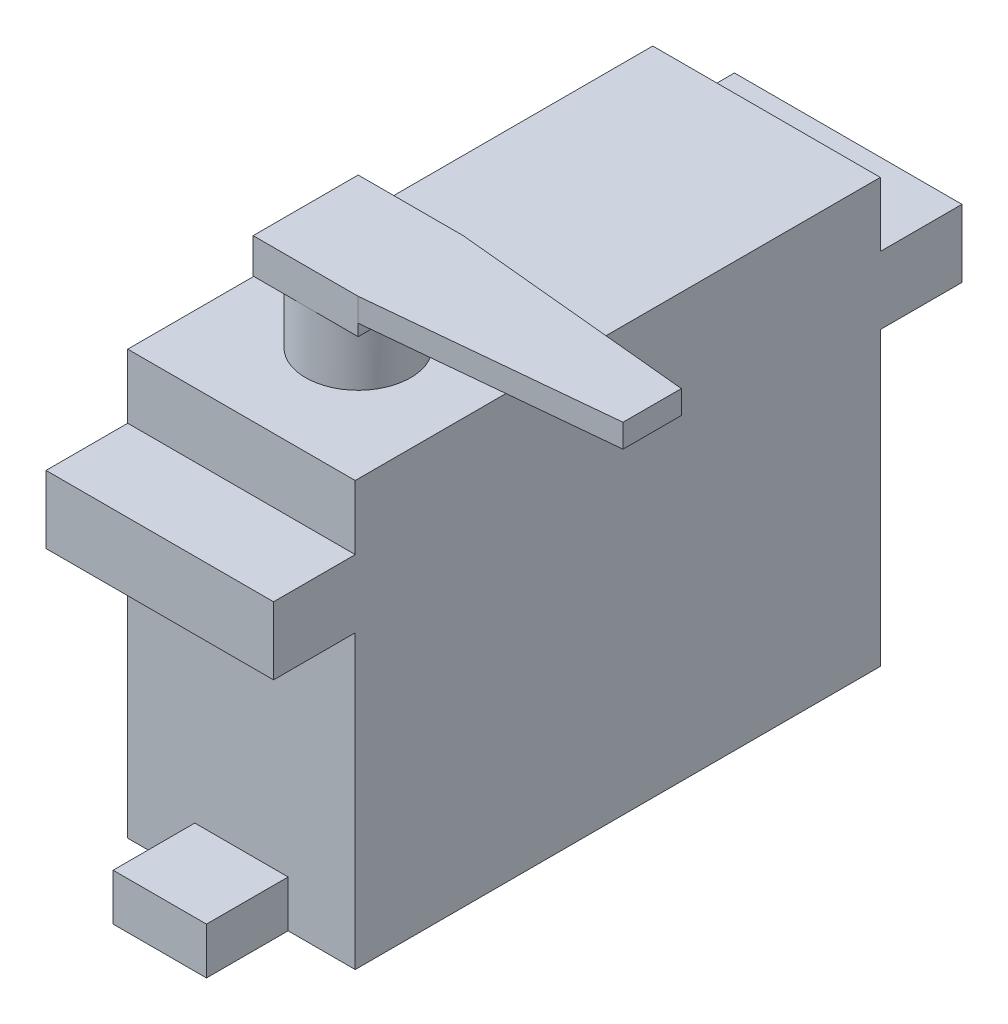
SolidWorks part; units mm, degrees
ref_plane "Front Plane" through (0, 0, 0) normal (0, 0, 1) x (1, 0, 0)
ref_plane "Top Plane" through (0, 0, 0) normal (0, 1, 0) x (1, 0, 0)
ref_plane "Right Plane" through (0, 0, 0) normal (1, 0, 0) x (0, 0, -1)
sketch "Sketch1" plane through (0, 0, 0) normal (1, 0, 0) x (0, 0, -1)
  line L0 (0, 0) -> (45, 0)
  line L1 (45, 0) -> (45, 25)
  line L2 (45, 25) -> (52, 25)
  line L3 (52, 25) -> (52, 30.8)
  line L4 (52, 30.8) -> (45, 30.8)
  line L5 (45, 30.8) -> (45, 36.3)
  line L6 (45, 36.3) -> (0, 36.3)
  line L7 (0, 36.3) -> (0, 30.8)
  line L8 (0, 30.8) -> (-7, 30.8)
  line L9 (-7, 30.8) -> (-7, 25)
  line L10 (-7, 25) -> (0, 25)
  line L11 (0, 25) -> (0, 0)
  dimension "D1" = 45
  dimension "D2" = 25
  dimension "D3" = 7
  dimension "D4" = 5.8
  dimension "D5" = 5.5
  dimension "D6" = 7
  dimension "D7" = 5.8
  dimension "D8" = 45
  dimension "D9" = 25
extrude "Boss-Extrude1" add sketch "Sketch1" along normal blind 19.5
sketch "Sketch2" plane through (0, 0, 0) normal (0, 0, 1) x (1, 0, 0)
  line L0 (0, 0) -> (9.75, 0) construction
  line L1 (19.5, 0) -> (0, 0) construction
  line L2 (9.75, 0) -> (9.75, 4) construction
  line L3 (9.75, 4) -> (5.75, 4) construction
  line L5 (5.75, 4) -> (13.75, 4)
  line L6 (5.75, 4) -> (5.75, 0)
  line L7 (5.75, 0) -> (13.75, 0)
  line L8 (13.75, 4) -> (13.75, 0)
  dimension "D1" = 4
  dimension "D2" = 4
  dimension "D3" = 8
extrude "Boss-Extrude2" add sketch "Sketch2" along normal blind 7
sketch "Sketch3" plane through (0, 36.3, 0) normal (0, 1, 0) x (1, 0, 0)
  line L0 (0, 45) -> (0, 0) construction
  line L1 (19.5, 0) -> (0, 0) construction
  circle A0 centre (9.75, 10) radius 4.5
  dimension "D3" = 9
  dimension "D1" = 9.75
  dimension "D2" = 10
extrude "Boss-Extrude3" add sketch "Sketch3" along normal blind 5.3 contours A0
sketch "Sketch4" plane through (0, 41.6, 0) normal (0, 1, 0) x (1, 0, 0)
  line L1 (14.25, 5.5) -> (5.25, 5.5)
  line L2 (14.25, 5.5) -> (14.25, 14.5)
  line L3 (14.25, 14.5) -> (5.25, 14.5)
  line L4 (5.25, 5.5) -> (5.25, 14.5)
  line L5 (14.25, 5.5) -> (5.25, 14.5) construction
  line L6 (14.25, 14.5) -> (5.25, 5.5) construction
  point P0 (9.75, 10)
  dimension "D1" = 9
extrude "Boss-Extrude4" add sketch "Sketch4" along normal blind 1
sketch "Sketch5" plane through (0, 42.6, 0) normal (0, 1, 0) x (1, 0, 0)
  line L0 (14.25, 5.5) -> (14.25, 14.5) construction
  line L1 (5.25, 14.5) -> (14.25, 14.5)
  line L2 (5.25, 14.5) -> (5.25, 5.5)
  line L3 (5.25, 5.5) -> (14.25, 5.5)
  line L5 (5.25, 10) -> (34.95, 10) construction
  line L6 (34.95, 10) -> (34.95, 12.5)
  line L7 (34.95, 12.5) -> (14.25, 14.5)
  line L8 (34.95, 10) -> (34.95, 7.5)
  line L9 (14.25, 5.5) -> (34.95, 7.5)
  dimension "D1" = 29.7
  dimension "D2" = 2.5
  dimension "D3" = 2.5
  dimension "D4" = 2
extrude "Boss-Extrude5" add sketch "Sketch5" along normal blind 2 contours L9 L8 L6 L7 L1 L2 L3
